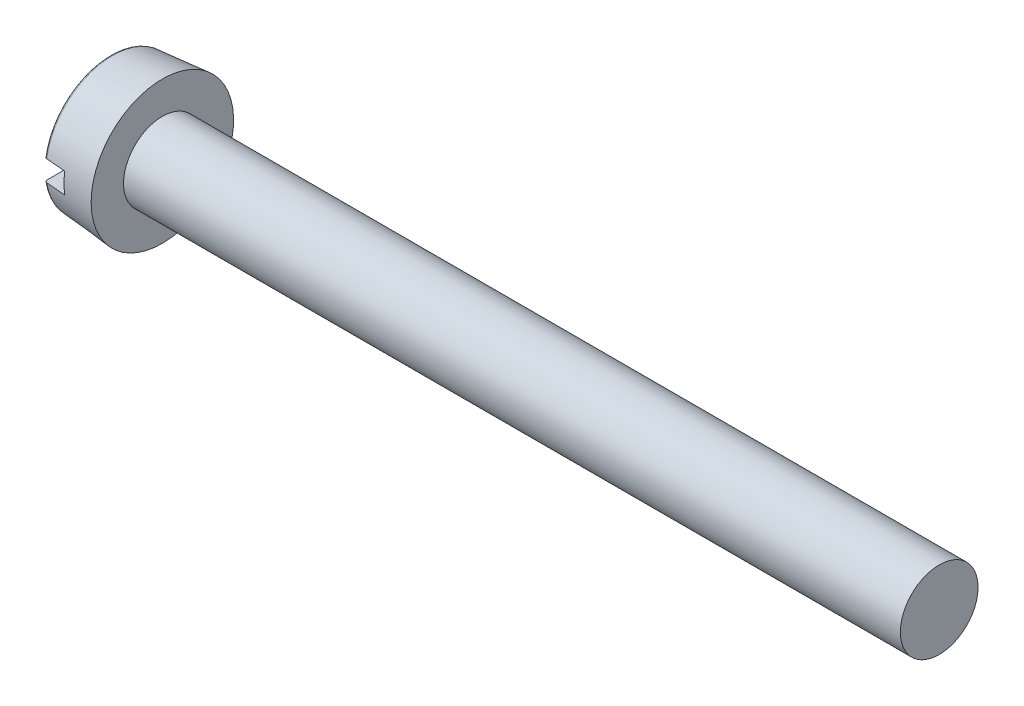
SolidWorks part; units mm, degrees
ref_plane "Plane1" through (0, 0, 0) normal (0, 0, 1) x (1, 0, 0)
ref_plane "Plane2" through (0, 0, 0) normal (0, 1, 0) x (1, 0, 0)
ref_plane "Plane3" through (0, 0, 0) normal (1, 0, 0) x (0, 0, -1)
sketch "BodySke" plane through (0, 0, 0) normal (0, 0, 1) x (1, 0, 0)
  line L0 (2, 1.5) -> (2, 2.75)
  line L1 (0, 0) -> (0, 2.575)
  line L2 (-25.4, 0) -> (127, 0) construction
  line L3 (32, 0) -> (0, 0)
  line L4 (2, 1.5) -> (32, 1.5)
  line L5 (32, 1.5) -> (32, 0)
  line L6 (0, 2.575) -> (2, 2.75)
  line L9 (2.5, 3.0875) -> (2.5, -6.4375) construction
  line L10 (2, 6.35) -> (2, -3.175) construction
  dimension "Length" = 30
  dimension "Head_ht" = 2
  dimension "Advance" = 0.5
  dimension "Thread_nom" = 30
  dimension "Head_dia" = 5.5
  dimension "Head_side_angle" = 5
  dimension "Diameter" = 3
revolve "Base-Revolve" add sketch "BodySke"
cosmetic thread "ThreadCosmetic"
fillet "Fillet1" [suppressed] radius 0.1
fillet "Fillet2" radius 0.1 1 edges at (0, 0, 2.575)
sketch "Sketch2" plane through (0, 0, 0) normal (1, 0, 0) x (0, 0, -1)
  line L0 (2.75, -0.4) -> (-2.75, -0.4)
  line L1 (2.75, -0.4) -> (2.75, 0.4)
  line L2 (-2.75, 0.4) -> (2.75, 0.4)
  line L3 (-2.75, 0.4) -> (-2.75, -0.4)
  dimension "D1" = 5.5
  dimension "Slot_width" = 0.8
  dimension "D2" = 2.75
  dimension "D3" = 0.4
extrude "Slot" cut sketch "Sketch2" along normal blind 0.85
sketch "ThdSchSke" plane through (0, 0, 0) normal (0, 0, 1) x (1, 0, 0)
  line L0 (3, -1.2195) -> (2.8036, -1.5)
  line L1 (3, -1.2195) -> (3.1964, -1.5)
  line L2 (3.1964, -1.5) -> (3.1964, -1.875)
  line L3 (-3.175, 0) -> (5.1513, 0) construction
  line L5 (3.1964, -1.875) -> (2.8036, -1.875)
  line L6 (2.8036, -1.875) -> (2.8036, -1.5)
  dimension "Diameter" = 3
  dimension "SideAngle" = 55
  dimension "VeeAngle" = 70
  dimension "Thread_minor" = 2.439
  dimension "Overcut" = 3.75
  dimension "Start" = 3
revolve "ThreadSchematic" [suppressed] cut sketch "ThdSchSke" angle 360 about L3
pattern_linear "ThdSchPat" [suppressed]
equation "\"D1@Sketch2\" = \"Head_dia@BodySke\""
equation "\"D2@Sketch2\" = \"D1@Sketch2\" / 2"
equation "\"D3@Sketch2\" = \"Slot_width@Sketch2\" / 2"
equation "\"Thread_length@ThreadCosmetic\" = ((sgn( (\"Length@BodySke\" - \"Advance@BodySke\" * 2.0 ) - \"Thread_nom@BodySke\" )-1)*( (\"Length@BodySke\" - \"Advance@BodySke\"  * 2.0) - \"Thread_nom@BodySke\" ))/-2+ \"Thread_nom@BodySke\""
equation "\"Thread_minor@ThdSchSke\" = \"Thread_minor@ThreadCosmetic\""
equation "\"Diameter@ThdSchSke\" = \"Diameter@BodySke\""
equation "\"Overcut@ThdSchSke\" = \"Diameter@BodySke\" * 1.25"
equation "\"Start@ThdSchSke\" = \"Head_ht@BodySke\" + \"Length@BodySke\" - \"Thread_length@ThreadCosmetic\"  '---Non-countersunk---"
equation "\"Num_threads@ThdSchPat\" = int( \"Thread_length@ThreadCosmetic\" / \"Advance@BodySke\" + 0.999 )  + 1"
equation "\"Advance@ThdSchPat\" = \"Thread_length@ThreadCosmetic\" /  (\"Num_threads@ThdSchPat\" - 1) 'relax it"
